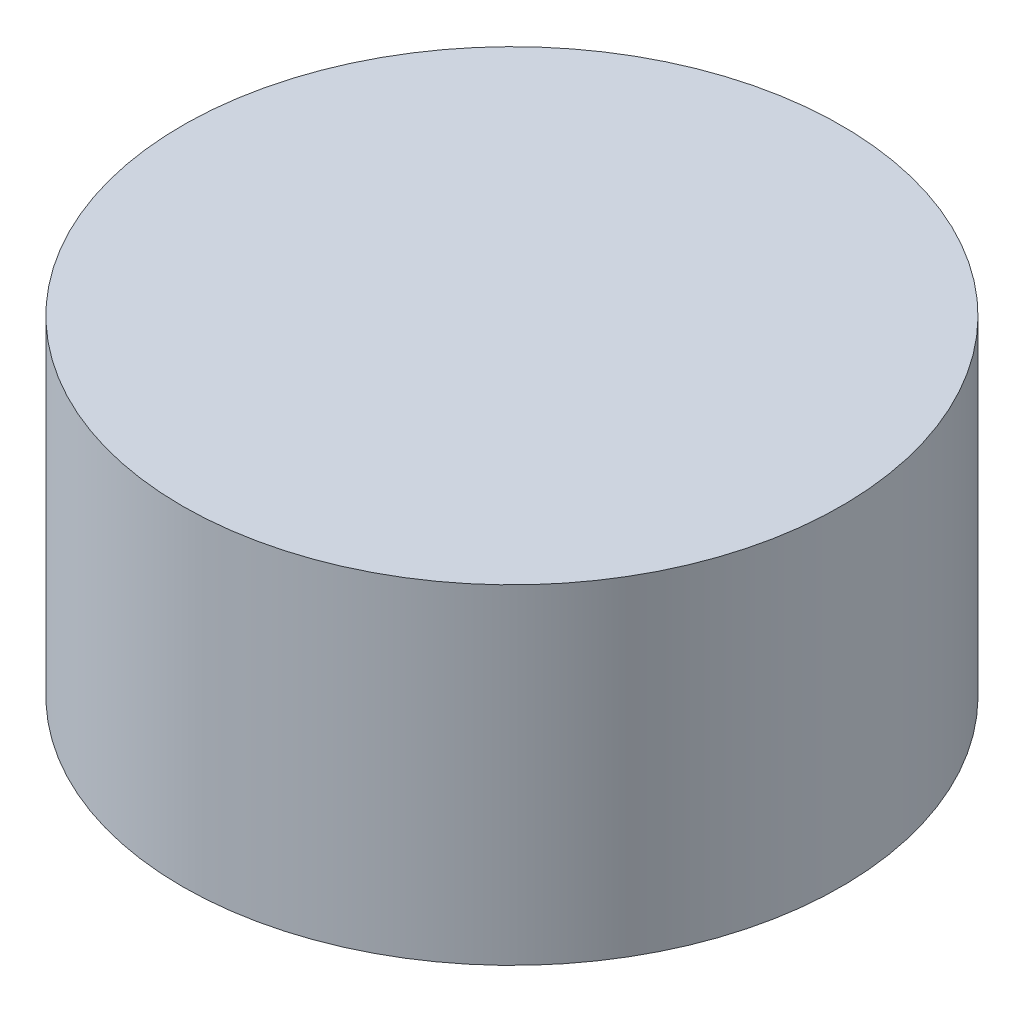
SolidWorks part; units mm, degrees
ref_plane "Front Plane" through (0, 0, 0) normal (0, 0, 1) x (1, 0, 0)
ref_plane "Top Plane" through (0, 0, 0) normal (0, 1, 0) x (1, 0, 0)
ref_plane "Right Plane" through (0, 0, 0) normal (1, 0, 0) x (0, 0, -1)
sketch "Sketch2" plane through (0, 0, 0) normal (0, 1, 0) x (1, 0, 0)
  circle A0 centre (0, 0) radius 10
  dimension "D1" = 20
extrude "Boss-Extrude1" add sketch "Sketch2" along normal blind 10
